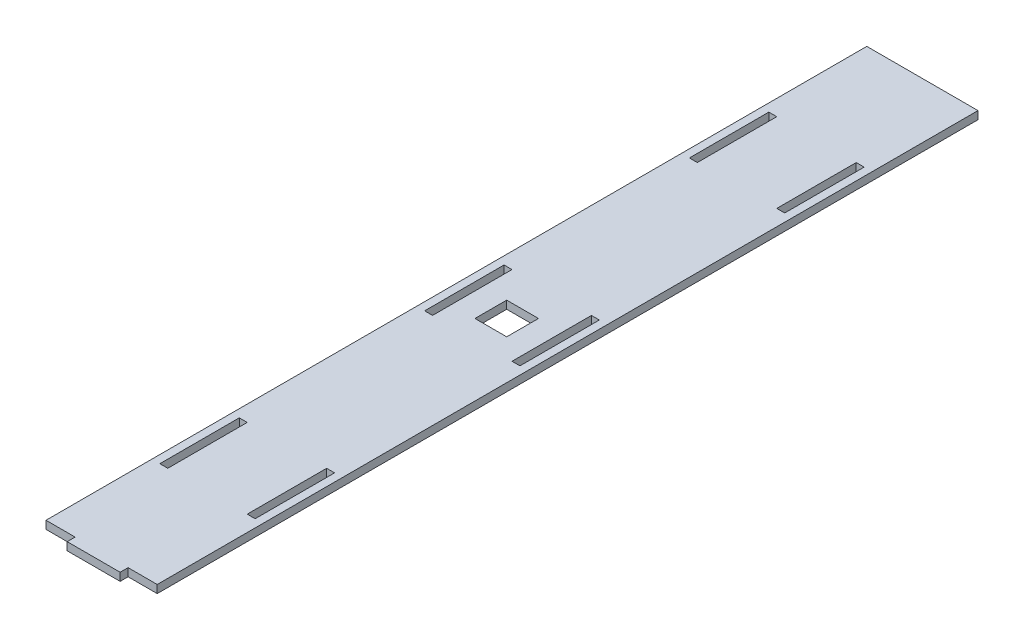
SolidWorks part; units mm, degrees
material "ABS"
ref_plane "Front Plane" through (0, 0, 0) normal (0, 0, 1) x (1, 0, 0)
ref_plane "Top Plane" through (0, 0, 0) normal (0, 1, 0) x (1, 0, 0)
ref_plane "Right Plane" through (0, 0, 0) normal (1, 0, 0) x (0, 0, -1)
sketch "Sketch1" plane through (0, 0, 0) normal (0, 1, 0) x (1, 0, 0)
  line L0 (31, 0) -> (42, 0)
  line L1 (0, 0) -> (11, 0)
  line L2 (0, 0) -> (0, 310)
  line L3 (0, 310) -> (42, 310)
  line L4 (42, 0) -> (42, 310)
  line L6 (11, 0) -> (11, -3)
  line L7 (11, -3) -> (31, -3)
  line L8 (31, 0) -> (31, -3)
  line L9 (36, 70) -> (39, 70)
  line L10 (36, 70) -> (36, 40)
  line L11 (36, 40) -> (39, 40)
  line L12 (39, 70) -> (39, 40)
  line L13 (36, 170) -> (39, 170)
  line L14 (36, 170) -> (36, 140)
  line L15 (36, 140) -> (39, 140)
  line L16 (39, 170) -> (39, 140)
  line L17 (36, 270) -> (39, 270)
  line L18 (36, 270) -> (36, 240)
  line L19 (36, 240) -> (39, 240)
  line L20 (39, 270) -> (39, 240)
  line L21 (21, -3) -> (21, 45.3243) construction
  line L22 (3, 270) -> (3, 240)
  line L23 (6, 240) -> (3, 240)
  line L24 (6, 270) -> (6, 240)
  line L25 (6, 270) -> (3, 270)
  line L26 (3, 170) -> (3, 140)
  line L27 (6, 140) -> (3, 140)
  line L28 (6, 170) -> (6, 140)
  line L29 (6, 170) -> (3, 170)
  line L30 (3, 70) -> (3, 40)
  line L31 (6, 40) -> (3, 40)
  line L32 (6, 70) -> (6, 40)
  line L33 (6, 70) -> (3, 70)
  line L35 (15, 159) -> (27, 159)
  line L36 (15, 159) -> (15, 147)
  line L37 (15, 147) -> (27, 147)
  line L38 (27, 159) -> (27, 147)
  dimension "D1" = 310
  dimension "D2" = 42
  dimension "D3" = 20
  dimension "D4" = 3
  dimension "D5" = 11
  dimension "D6" = 40
  dimension "D7" = 30
  dimension "D8" = 3
  dimension "D9" = 3
  dimension "D10" = 70
  dimension "D11" = 3
  dimension "D12" = 30
  dimension "D13" = 3
  dimension "D14" = 30
  dimension "D15" = 3
  dimension "D16" = 3
  dimension "D17" = 70
  dimension "D18" = 12
  dimension "D19" = 12
  dimension "D20" = 150
  dimension "D21" = 15
extrude "Boss-Extrude1" add sketch "Sketch1" along normal blind 3
